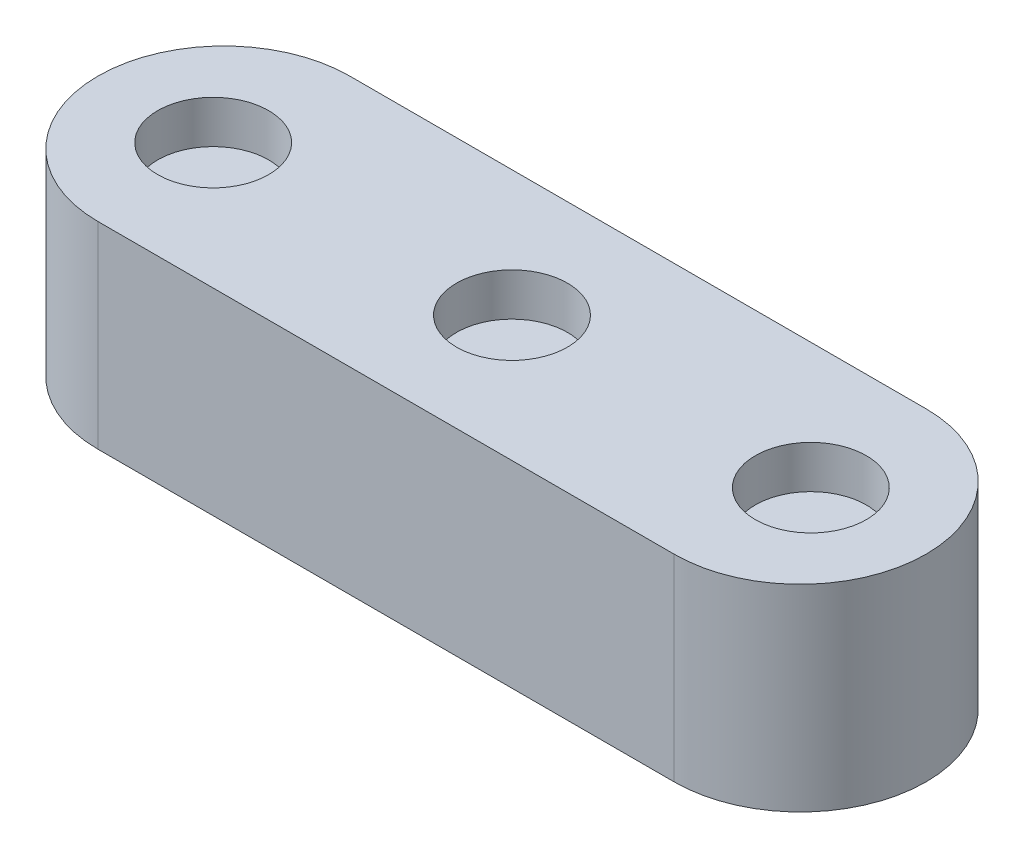
SolidWorks part; units mm, degrees
ref_plane "Front Plane" through (0, 0, 0) normal (0, 0, 1) x (1, 0, 0)
ref_plane "Top Plane" through (0, 0, 0) normal (0, 1, 0) x (1, 0, 0)
ref_plane "Right Plane" through (0, 0, 0) normal (1, 0, 0) x (0, 0, -1)
sketch "Sketch1" plane through (0, 0, 0) normal (0, 1, 0) x (1, 0, 0)
  line L0 (-48.5, 0) -> (48.5, 0) construction
  line L1 (-48.5, 14.75) -> (48.5, 14.75) construction
  line L2 (-48.5, 14.75) -> (-48.5, -14.75) construction
  line L3 (-48.5, -14.75) -> (48.5, -14.75) construction
  line L4 (48.5, 14.75) -> (48.5, -14.75)
  line L5 (-48.5, 14.75) -> (48.5, -14.75) construction
  line L6 (-48.5, -14.75) -> (48.5, 14.75) construction
  line L7 (0, 0) -> (0, 14.75) construction
  line L8 (-33.75, 14.75) -> (33.75, 14.75)
  line L9 (-33.75, -14.75) -> (33.75, -14.75)
  circle A0 centre (33.75, 0) radius 14.75 construction
  circle A1 centre (-33.75, 0) radius 14.75 construction
  arc A2 (-33.75, -14.75) -> (-33.75, 14.75) centre (-33.75, 0) cw
  arc A3 (33.75, 14.75) -> (33.75, -14.75) centre (33.75, 0) cw
  point P0 (0, 0)
  dimension "D1" = 97
  dimension "D2" = 29.5
extrude "Boss-Extrude1" add sketch "Sketch1" along normal blind 23.1 contours A3 L8 A2 L9
sketch "Sketch2" plane through (0, 23.1, 0) normal (0, 1, 0) x (1, 0, 0)
  line L0 (-48.5, 0) -> (48.5, 0) construction
  arc A0 (-33.75, 14.75) -> (-33.75, -14.75) centre (-33.75, 0) ccw construction
  arc A1 (33.75, -14.75) -> (33.75, 14.75) centre (33.75, 0) ccw construction
  circle A2 centre (0, 0) radius 6.5
  circle A3 centre (-35, 0) radius 6.5
  circle A4 centre (35, 0) radius 6.5
  dimension "D3" = 13
  dimension "D1" = 35
  dimension "D2" = 35
extrude "Cut-Extrude1" cut sketch "Sketch2" against normal blind 5
